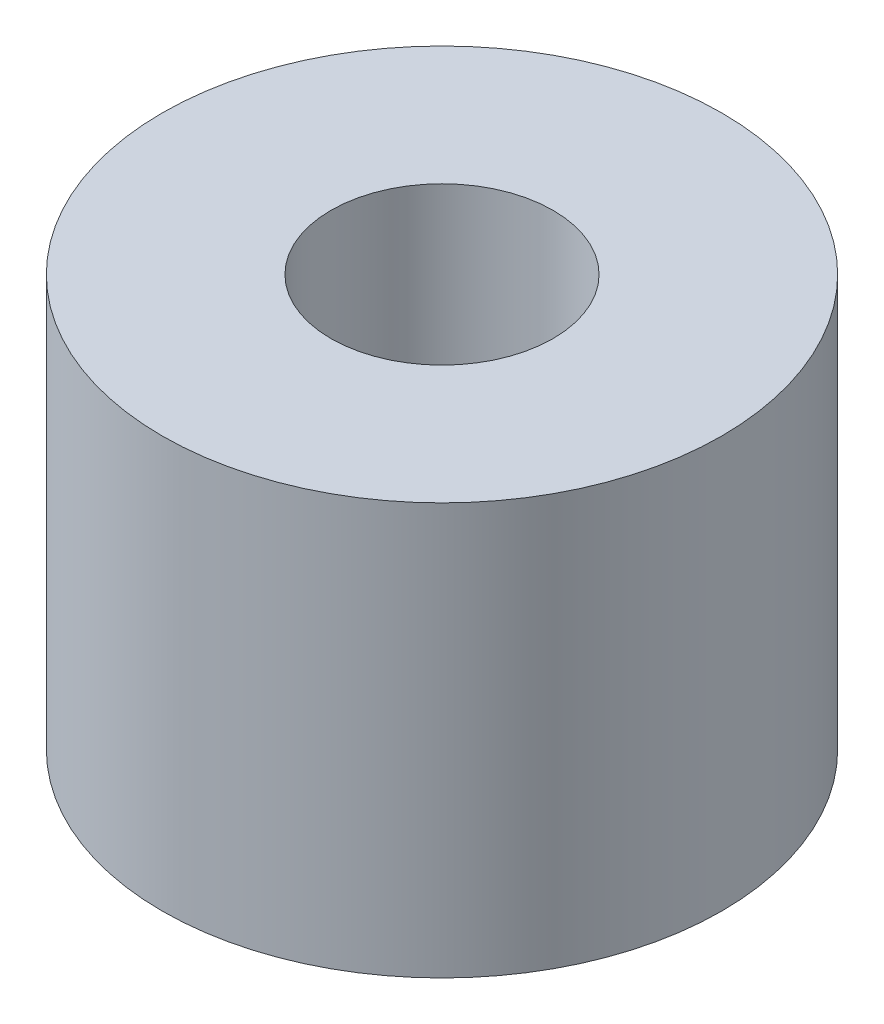
SolidWorks part; units mm, degrees
material "Oak"
ref_plane "Front Plane" through (0, 0, 0) normal (0, 0, 1) x (1, 0, 0)
ref_plane "Top Plane" through (0, 0, 0) normal (0, 1, 0) x (1, 0, 0)
ref_plane "Right Plane" through (0, 0, 0) normal (1, 0, 0) x (0, 0, -1)
sketch "Sketch1" plane through (0, 0, 0) normal (0, 1, 0) x (1, 0, 0)
  circle A0 centre (0, 0) radius 1.7145
  circle A1 centre (0, 0) radius 4.318
  dimension "D1" = 3.429
  dimension "D2" = 8.636
extrude "Boss-Extrude1" add sketch "Sketch1" along normal blind 6.35
